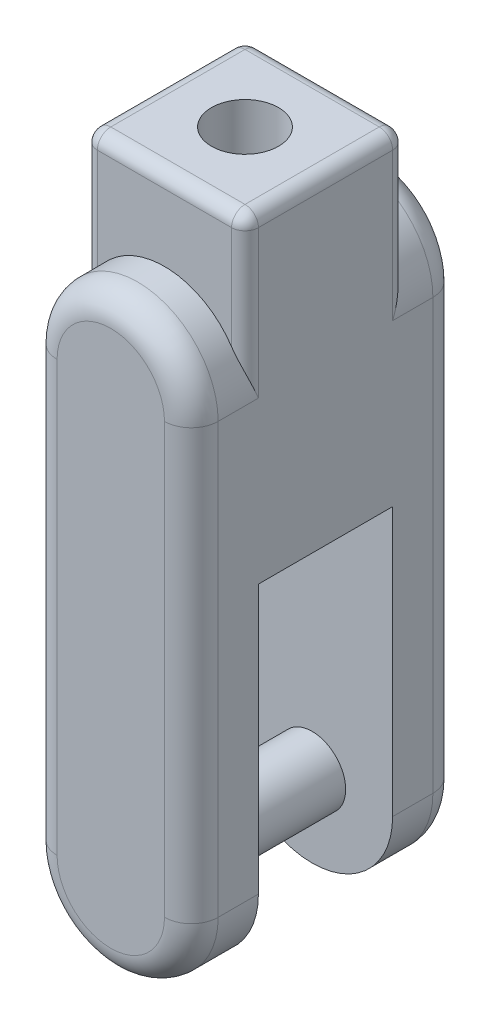
SolidWorks part; units mm, degrees
ref_plane "Front Plane" through (0, 0, 0) normal (0, 0, 1) x (1, 0, 0)
ref_plane "Top Plane" through (0, 0, 0) normal (0, 1, 0) x (1, 0, 0)
ref_plane "Right Plane" through (0, 0, 0) normal (1, 0, 0) x (0, 0, -1)
sketch "Sketch2" plane through (0, 0, 0) normal (1, 0, 0) x (0, 0, -1)
  line L0 (0, 0) -> (0, 45) construction
  line L2 (-30, -37.5) -> (30, -37.5)
  line L3 (-30, -37.5) -> (-30, 82.5)
  line L4 (-30, 82.5) -> (30, 82.5)
  line L5 (30, -37.5) -> (30, 82.5)
  line L6 (-30, -37.5) -> (30, 82.5) construction
  line L7 (-30, 82.5) -> (30, -37.5) construction
  point P3 (0, 22.5)
  dimension "D1" = 45
  dimension "D2" = 60
  dimension "D3" = 120
extrude "Boss-Extrude1" add sketch "Sketch2" against normal blind 60
sketch "Sketch5" plane through (0, 82.5, 0) normal (0, 1, 0) x (1, 0, 0)
  line L0 (-60, 30) -> (0, 30) construction
  line L1 (0, 30) -> (0, -30) construction
  circle A0 centre (-30, 0) radius 12.5
  dimension "D1" = 25
  dimension "D2" = 30
  dimension "D3" = 30
extrude "Cut-Extrude2" cut sketch "Sketch5" against normal blind 48
sketch "Sketch6" plane through (0, 0, 30) normal (0, 0, 1) x (1, 0, 0)
  line L0 (-30, 22.5) -> (-30, -137.5) construction
  line L1 (0, 22.5) -> (0, -137.5)
  line L2 (-60, 22.5) -> (-60, -137.5)
  line L3 (0, 82.5) -> (0, -37.5) construction
  line L4 (-60, 82.5) -> (0, 82.5) construction
  arc A0 (0, 22.5) -> (-60, 22.5) centre (-30, 22.5) ccw
  arc A1 (-60, -137.5) -> (0, -137.5) centre (-30, -137.5) ccw
  point P2 (-30, -57.5)
  dimension "D2" = 30
  dimension "D1" = 30
  dimension "D3" = 60
  dimension "D4" = 160
extrude "Boss-Extrude3" add sketch "Sketch6" along normal blind 20 and the other way blind 5
ref_plane "Plane1" through (0, 0, 0) normal (0, 0, -1) x (-1, 0, 0)
fillet "Fillet3" radius 5 8 edges at (0, 82.5, 0) (-60, 82.5, 0) (0, 52.5, 30) (-60, 52.5, 30) (-30, 82.5, 30) (0, 22.5, -30) (-60, 22.5, -30) (-30, 82.5, -30)
mirror "Mirror2" about plane through (0, 0, 0) normal (0, 0, -1) of bodies 105
fillet "Fillet4" radius 10 4 edges at (0, -57.5, 50) (-30, -167.5, 50) (-60, -57.5, 50) (-30, 52.5, 50)
fillet "Fillet5" radius 10 4 edges at (-60, -57.5, -50) (-30, -167.5, -50) (0, -57.5, -50) (-30, 52.5, -50)
fillet "Fillet6" radius 5 5 edges at (-58.5355, -37.5, -28.5355) (-30, -37.5, -30) (-1.4645, -37.5, -28.5355) (-60, -37.5, 0) (0, -37.5, 0)
sketch "Sketch7" plane through (0, 0, 25) normal (0, 0, -1) x (-1, 0, 0)
  circle A0 centre (30, -137.5) radius 12.5
  dimension "D1" = 25
extrude "Boss-Extrude4" add sketch "Sketch7" along normal up to surface (50 mm away) up to face at (-30, -95, -25)
